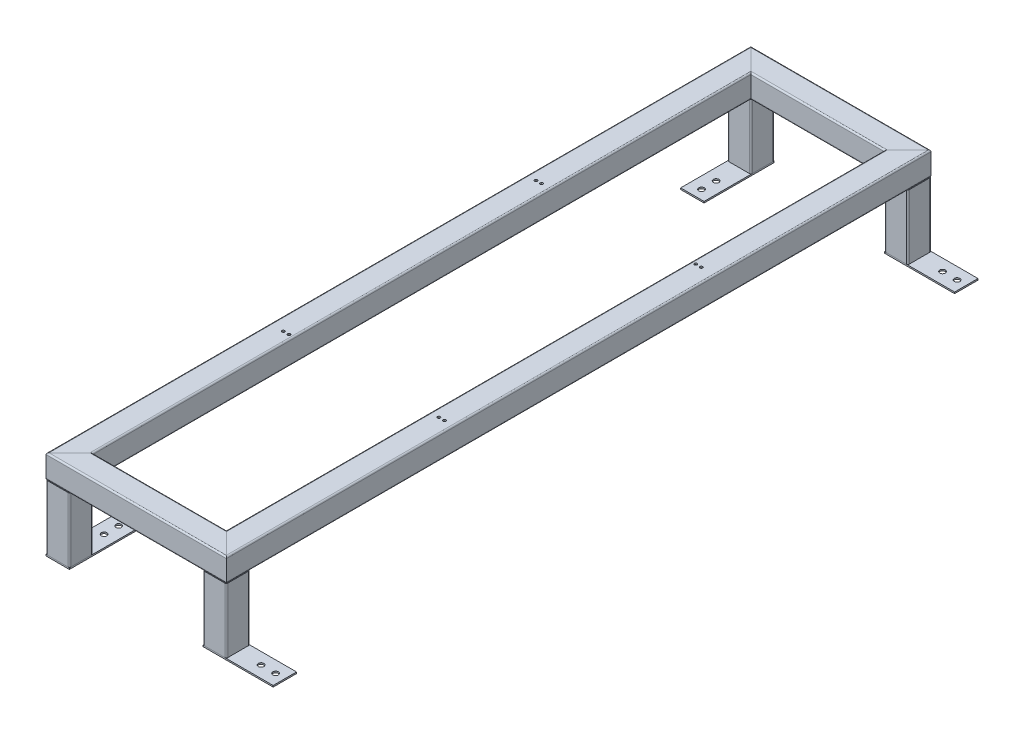
SolidWorks part; units mm, degrees
material "Acero galvanizado"
ref_plane "Front" through (0, 0, 0) normal (0, 0, 1) x (1, 0, 0)
ref_plane "Top" through (0, 0, 0) normal (0, 1, 0) x (1, 0, 0)
ref_plane "Right" through (0, 0, 0) normal (1, 0, 0) x (0, 0, -1)
sketch3d "Croquis3D1"
  line L1 (0, 0, 0) -> (0, 0, 714.4)
  line L2 (0, 0, 0) -> (145, 0, 0)
  line L3 (145, 0, 0) -> (145, 0, 714.4)
  line L4 (0, 0, 714.4) -> (145, 0, 714.4)
  line L5 (0, 0, 0) -> (145, 0, 714.4) construction
  line L6 (145, 0, 0) -> (0, 0, 714.4) construction
  line L14 (145, 0, 714.4) -> (145, -70, 714.4)
  line L15 (0, 0, 0) -> (-25.4, 0, 0) construction
  line L16 (-25.4, 0, 0) -> (-25.4, 0, -25.4) construction
  line L17 (0, 0, 714.4) -> (-25.4, 0, 714.4) construction
  line L18 (145, 0, 0) -> (145, 0, -25.4) construction
  line L19 (-25.4, 0, 714.4) -> (-25.4, -70, 714.4)
  line L20 (-25.4, 0, -25.4) -> (-25.4, -70, -25.4)
  line L21 (145, 0, -25.4) -> (145, -70, -25.4)
  point P4 (72.5, 0, 357.2)
  dimension "D3" = 70
  dimension "D1" = 145
  dimension "D2" = 714.4
other "Tubo cuadrada 1 X 1(1)"
ref_plane "Plano9" through (0, 12.7, 727.1) normal (1, 0, 0) x (0, 0, -1)
sketch "Croquis1" plane through (0, 12.7, 727.1) normal (1, 0, 0) x (0, 0, -1)
  line L5 (-11.1125, 11.1125) -> (-11.1125, -11.1125)
  line L13 (11.1125, 12.7) -> (-11.1125, 12.7)
  line L14 (12.7, 11.1125) -> (12.7, -11.1125)
  line L15 (11.1125, -12.7) -> (-11.1125, -12.7)
  line L16 (-12.7, 11.1125) -> (-12.7, -11.1125)
  line L17 (12.7, 12.7) -> (-12.7, -12.7) construction
  line L18 (12.7, -12.7) -> (-12.7, 12.7) construction
  line L19 (11.1125, -11.1125) -> (-11.1125, -11.1125)
  line L20 (11.1125, 11.1125) -> (11.1125, -11.1125)
  line L21 (11.1125, 11.1125) -> (-11.1125, 11.1125)
  line L22 (12.7, 12.7) -> (-12.7, 12.7) construction
  line L23 (12.7, 12.7) -> (12.7, -12.7) construction
  line L24 (12.7, -12.7) -> (-12.7, -12.7) construction
  line L25 (-12.7, 12.7) -> (-12.7, -12.7) construction
  arc A8 (11.1125, 12.7) -> (12.7, 11.1125) centre (11.1125, 11.1125) cw
  arc A9 (12.7, -11.1125) -> (11.1125, -12.7) centre (11.1125, -11.1125) cw
  arc A10 (-11.1125, -12.7) -> (-12.7, -11.1125) centre (-11.1125, -11.1125) cw
  arc A11 (-12.7, 11.1125) -> (-11.1125, 12.7) centre (-11.1125, 11.1125) cw
  point P0 (0, 0)
  point P6 (-12.7, 0)
  point P22 (-11.1125, 0)
  point P23 (11.1125, 0)
  point P24 (12.7, 0)
  point P25 (0, 11.1125)
  point P26 (0, 12.7)
  point P27 (0, -11.1125)
  point P28 (0, -12.7)
  point P29 (0, 0)
  dimension "D3" = 1.5875
  dimension "D2" = 1.5875
  dimension "D1" = 25.4
sketch "Croquis2" plane through (0, -70, 0) normal (0, -1, 0) x (1, 0, 0)
  line L0 (0, 714.4) -> (0, 0) construction
  line L1 (-25.4, 739.8) -> (0, 739.8)
  line L2 (-25.4, 739.8) -> (-25.4, 663.6)
  line L3 (-25.4, 663.6) -> (0, 663.6)
  line L4 (0, 739.8) -> (0, 663.6)
  line L5 (72.5, 738.2125) -> (72.5, -23.8125) construction
  line L6 (168.8125, 738.2125) -> (-23.8125, 738.2125) construction
  line L7 (-23.8125, -23.8125) -> (168.8125, -23.8125) construction
  line L8 (-23.8125, 357.2) -> (168.8125, 357.2) construction
  line L9 (-23.8125, 738.2125) -> (-23.8125, -23.8125) construction
  line L10 (168.8125, -23.8125) -> (168.8125, 738.2125) construction
  line L23 (-12.7, 663.6) -> (-12.7, 714.4) construction
  line L24 (-23.8125, 714.4) -> (-1.5875, 714.4) construction
  line L25 (-12.7, 714.4) -> (0, 689) construction
  line L34 (-12.7, 0) -> (0, 25.4) construction
  line L35 (-12.7, 50.8) -> (-12.7, 0) construction
  line L40 (0, -25.4) -> (0, 50.8)
  line L41 (-25.4, 50.8) -> (0, 50.8)
  line L42 (-25.4, -25.4) -> (-25.4, 50.8)
  line L43 (-25.4, -25.4) -> (0, -25.4)
  line L44 (221.2, 727.1) -> (170.4, 727.1) construction
  line L45 (145, 714.4) -> (221.2, 714.4)
  line L46 (145, 714.4) -> (145, 739.8)
  line L47 (145, 739.8) -> (221.2, 739.8)
  line L48 (221.2, 714.4) -> (221.2, 739.8)
  line L49 (170.4, 715.9875) -> (170.4, 738.2125) construction
  line L50 (221.2, -12.7) -> (170.4, -12.7) construction
  line L51 (221.2, 0) -> (221.2, -25.4)
  line L52 (145, -25.4) -> (221.2, -25.4)
  line L53 (145, 0) -> (145, -25.4)
  line L54 (145, 0) -> (221.2, 0)
  circle A0 centre (-12.7, 673.6) radius 3
  circle A1 centre (-12.7, 689.4) radius 3
  circle A6 centre (-12.7, 25) radius 3
  circle A7 centre (-12.7, 40.8) radius 3
  circle A10 centre (195.4, 727.1) radius 3
  circle A11 centre (211.2, 727.1) radius 3
  circle A12 centre (211.2, -12.7) radius 3
  circle A13 centre (195.4, -12.7) radius 3
  dimension "D2" = 6
  dimension "D3" = 6
  dimension "D7" = 6
  dimension "D8" = 6
  dimension "D1" = 76.2
  dimension "D4" = 10
  dimension "D5" = 25
  dimension "D6" = 76.2
  dimension "D9" = 10
  dimension "D10" = 25
extrude "Saliente-Extruir1" add sketch "Croquis2" along normal blind 1.5875 separate body
sketch "Croquis4" plane through (0, 0, 0) normal (0, -1, 0) x (1, 0, 0)
  circle A0 centre (155.8434, 209.6251) radius 1.5
  circle A1 centre (149.8434, 209.6251) radius 1.5
  circle A2 centre (160.5, 493.1309) radius 1.5
  circle A3 centre (154.5, 493.1309) radius 1.5
  circle A4 centre (-4.8434, 209.6251) radius 1.5
  circle A5 centre (-10.8434, 209.6251) radius 1.5
  circle A6 centre (-9.5, 493.1309) radius 1.5
  circle A7 centre (-15.5, 493.1309) radius 1.5
  dimension "D1" = 3
  dimension "D2" = 3
extrude "Cortar-Extruir1" cut sketch "Croquis4" against normal through all contours A5 | A4 | A7 | A6 | A2 | A3 | A1 | A0
sketch "Croquis5" plane through (0, 25.4, 0) normal (0, 1, 0) x (1, 0, 0)
  circle A0 centre (-15.5, -217.7) radius 1.5
  circle A1 centre (-9.5, -217.7) radius 1.5
  circle A2 centre (-10.8434, -496.7) radius 1.5
  circle A3 centre (-4.8434, -496.7) radius 1.5
  dimension "D1" = 3
  dimension "D2" = 3
  dimension "D3" = 3
  dimension "D4" = 3
extrude "Cortar-Extruir2" cut sketch "Croquis5" against normal blind 30 contours A0 | A1 | A2 | A3
